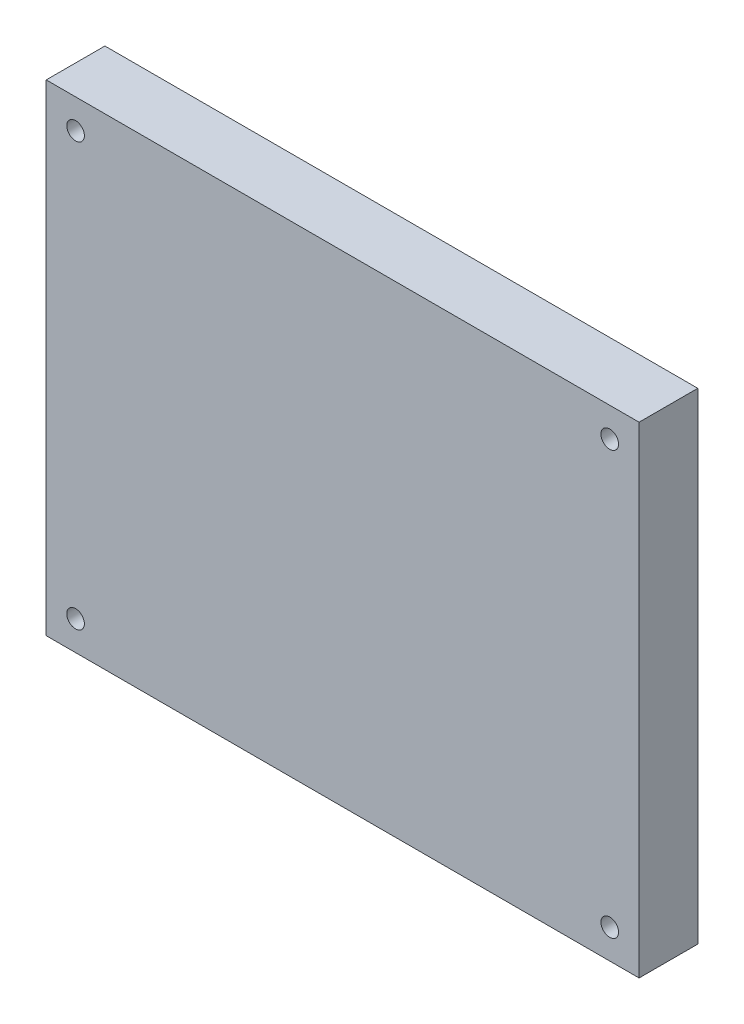
SolidWorks part; units mm, degrees
ref_plane "Plan de face" through (0, 0, 0) normal (0, 0, 1) x (1, 0, 0)
ref_plane "Plan de dessus" through (0, 0, 0) normal (0, 1, 0) x (1, 0, 0)
ref_plane "Plan de droite" through (0, 0, 0) normal (1, 0, 0) x (0, 0, -1)
sketch "Esquisse1" plane through (0, 0, 0) normal (0, 0, 1) x (1, 0, 0)
  line L1 (-24.5993, 14.9645) -> (76.4007, 14.9645)
  line L2 (-24.5993, 14.9645) -> (-24.5993, -67.0355)
  line L3 (-24.5993, -67.0355) -> (76.4007, -67.0355)
  line L4 (76.4007, 14.9645) -> (76.4007, -67.0355)
  dimension "D1" = 101
  dimension "D2" = 82
extrude "Extrusion1" add sketch "Esquisse1" along normal blind 10
sketch "Esquisse2" plane through (0, 0, 10) normal (0, 0, 1) x (1, 0, 0)
  line L0 (-24.5993, 14.9645) -> (-24.5993, -67.0355) construction
  line L2 (76.4007, 14.9645) -> (-24.5993, 14.9645) construction
  line L3 (76.4007, -67.0355) -> (76.4007, 14.9645) construction
  line L4 (-24.5993, -67.0355) -> (76.4007, -67.0355) construction
  circle A0 centre (-19.5993, 9.9645) radius 1.5
  circle A1 centre (71.4007, 9.9645) radius 1.5
  circle A2 centre (71.4007, -62.0355) radius 1.5
  circle A3 centre (-19.5993, -62.0355) radius 1.5
  point P12 (-22.0002, 14.9645)
  dimension "D1" = 5
  dimension "D3" = 5
  dimension "D2" = 5
  dimension "D4" = 5
  dimension "D5" = 5
  dimension "D6" = 5
  dimension "D7" = 5
  dimension "D8" = 5
extrude "Extrusion2" cut sketch "Esquisse2" against normal blind 10
